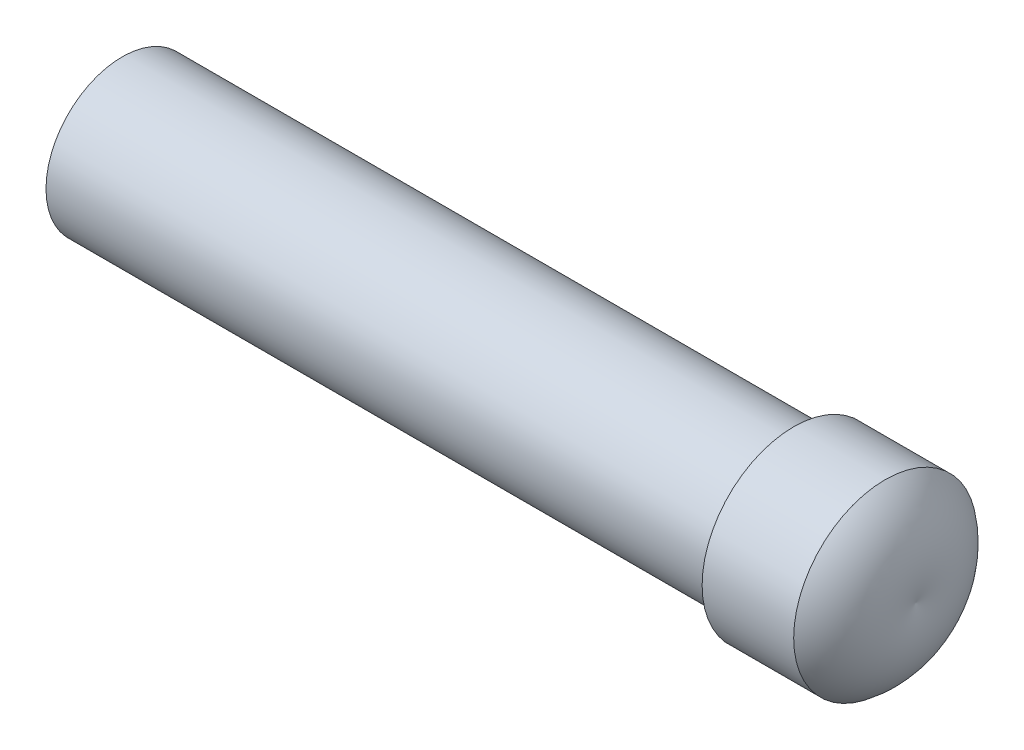
SolidWorks part; units mm, degrees
ref_plane "前基準面" through (0, 0, 0) normal (0, 0, 1) x (1, 0, 0)
ref_plane "上基準面" through (0, 0, 0) normal (0, 1, 0) x (1, 0, 0)
ref_plane "右基準面" through (0, 0, 0) normal (1, 0, 0) x (0, 0, -1)
sketch "草圖1" plane through (0, 0, 0) normal (0, 0, 1) x (1, 0, 0)
  line L0 (0, 0) -> (138.9413, 0) construction
  line L1 (0, 0) -> (0, 12.5)
  line L2 (0, 12.5) -> (110, 12.5)
  line L3 (110, 12.5) -> (110, 15)
  line L4 (110, 15) -> (125, 15)
  line L5 (0, 0) -> (130, 0)
  arc A0 (125, 15) -> (130, 0) centre (116.9088, 3.9696) cw
  dimension "D3" = 130
  dimension "D1" = 25
  dimension "D2" = 30
  dimension "D4" = 110
  dimension "D5" = 15
revolve "旋轉1" add sketch "草圖1" angle 360 about L0
